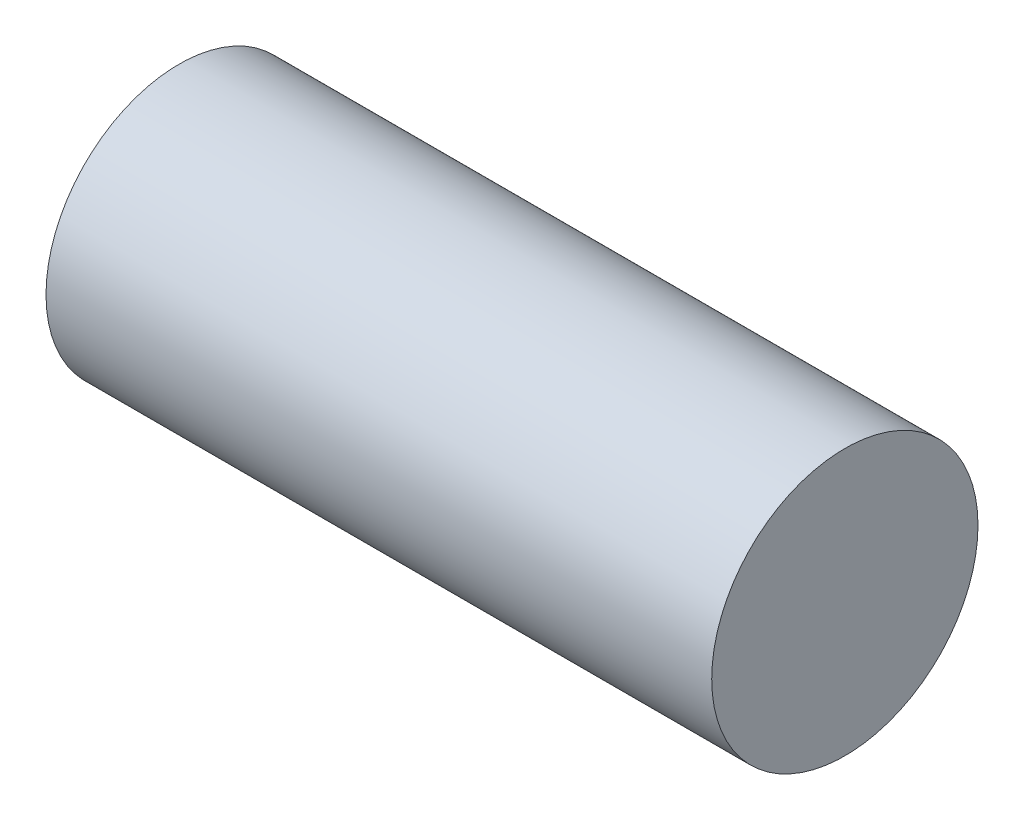
SolidWorks part; units mm, degrees
material "AISI Type A2 Tool Steel"
ref_plane "Front Plane" through (0, 0, 0) normal (1, 0, 0) x (0, 1, 0)
ref_plane "Top Plane" through (0, 0, 0) normal (0, 0, 1) x (0, 1, 0)
ref_plane "Right Plane" through (0, 0, 0) normal (0, 1, 0) x (-1, 0, 0)
sketch "Sketch1" plane through (0, 0, 0) normal (1, 0, 0) x (0, 1, 0)
  circle A0 centre (0, 0) radius 5
  dimension "D1" = 10
extrude "Boss-Extrude1" add sketch "Sketch1" along normal mid plane 25
